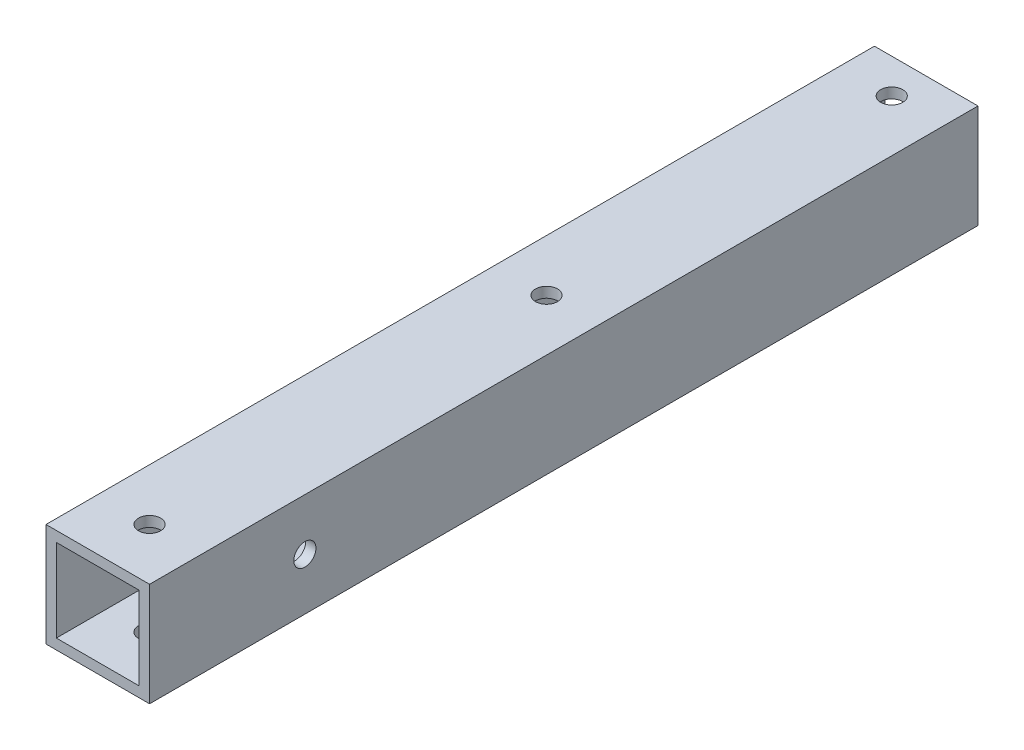
SolidWorks part; units mm, degrees
ref_plane "Front" through (0, 0, 0) normal (0, 0, 1) x (1, 0, 0)
ref_plane "Top" through (0, 0, 0) normal (0, 1, 0) x (1, 0, 0)
ref_plane "Right" through (0, 0, 0) normal (1, 0, 0) x (0, 0, -1)
sketch "ｽｹｯﾁ1" plane through (0, 0, 0) normal (0, 0, 1) x (1, 0, 0)
  line L0 (-6, 6) -> (6, 6)
  line L1 (-7.5, 7.5) -> (7.5, 7.5)
  line L2 (-7.5, 7.5) -> (-7.5, -7.5)
  line L3 (-7.5, -7.5) -> (7.5, -7.5)
  line L4 (7.5, 7.5) -> (7.5, -7.5)
  line L5 (0, -7.5) -> (0, 7.5) construction
  line L6 (-7.5, 0) -> (7.5, 0) construction
  line L7 (6, 6) -> (6, -6)
  line L8 (-6, -6) -> (6, -6)
  line L9 (-6, 6) -> (-6, -6)
  point P0 (0, 0)
  dimension "D1" = 15
  dimension "D2" = 15
  dimension "D3" = 1.5
extrude "ﾎﾞｽ - 押し出し1" add sketch "ｽｹｯﾁ1" along normal blind 120
sketch "ｽｹｯﾁ2" plane through (0, 7.5, 0) normal (0, 1, 0) x (1, 0, 0)
  line L0 (7.5, -120) -> (7.5, 0) construction
  line L1 (7.5, -120) -> (-7.5, -120) construction
  line L2 (7.5, 0) -> (-7.5, 0) construction
  circle A0 centre (0, -5) radius 1.6
  circle A1 centre (0, -112.5) radius 1.6
  circle A2 centre (0, -55) radius 1.6
  dimension "D1" = 3.2
  dimension "D2" = 3.2
  dimension "D3" = 7.5
  dimension "D4" = 7.5
  dimension "D5" = 7.5
  dimension "D6" = 5
  dimension "D7" = 3.2
  dimension "D8" = 7.5
  dimension "D9" = 50
extrude "ｶｯﾄ - 押し出し1" cut sketch "ｽｹｯﾁ2" against normal through all
sketch "ｽｹｯﾁ3" plane through (7.5, 0, 0) normal (1, 0, 0) x (0, 0, -1)
  line L0 (-120, -7.5) -> (0, -7.5) construction
  line L1 (-120, -7.5) -> (-120, 7.5) construction
  circle A0 centre (-97.5, 0) radius 1.6
  dimension "D1" = 3.2
  dimension "D3" = 7.5
  dimension "D5" = 22.5
extrude "ｶｯﾄ - 押し出し2" cut sketch "ｽｹｯﾁ3" against normal through all
